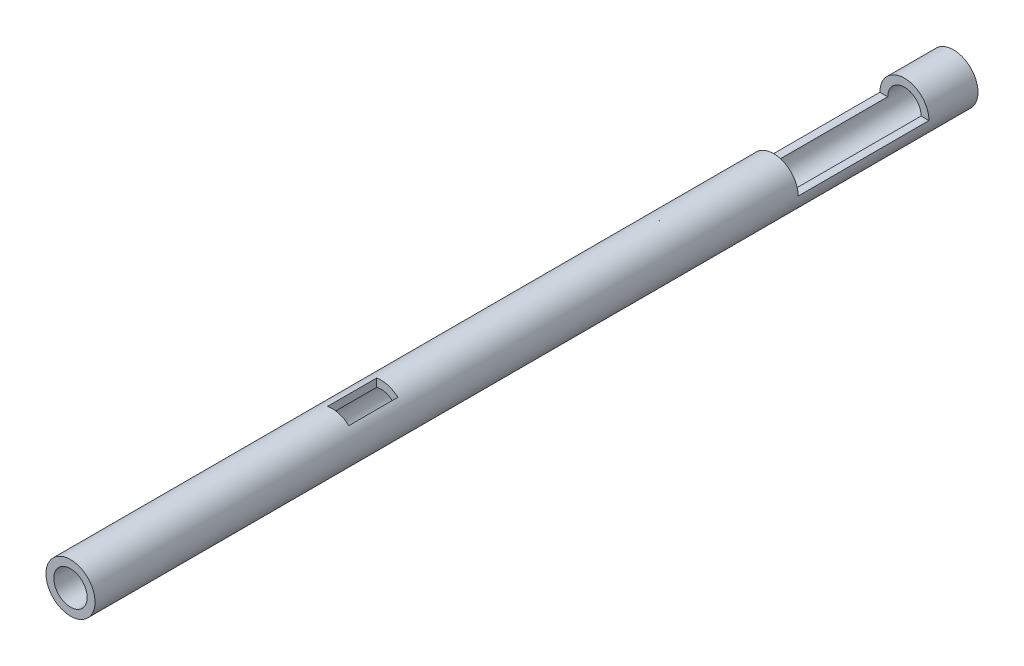
SolidWorks part; units mm, degrees
ref_plane "Front" through (0, 0, 0) normal (0, 0, 1) x (1, 0, 0)
ref_plane "Top" through (0, 0, 0) normal (0, 1, 0) x (1, 0, 0)
ref_plane "Right" through (0, 0, 0) normal (1, 0, 0) x (0, 0, -1)
sketch "Sketch2" plane through (0, 0, 0) normal (0, 0, 1) x (1, 0, 0)
  circle A0 centre (0, 0) radius 12.954
  circle A1 centre (0, 0) radius 19.05
  dimension "D1" = 38.1
  dimension "D2" = 25.908
extrude "Boss-Extrude1" add sketch "Sketch2" along normal blind 685.8
sketch "Sketch3" plane through (0, 0, 0) normal (0, 1, 0) x (1, 0, 0)
  line L0 (19.05, 0) -> (-19.05, 0) construction
  line L1 (-25.4, -38.1) -> (25.4, -38.1)
  line L2 (-25.4, -38.1) -> (-25.4, -139.7)
  line L3 (-25.4, -139.7) -> (25.4, -139.7)
  line L4 (25.4, -38.1) -> (25.4, -139.7)
  line L5 (-25.4, -38.1) -> (25.4, -139.7) construction
  line L6 (-25.4, -139.7) -> (25.4, -38.1) construction
  line L7 (0, 0) -> (0, -161.8795) construction
  point P4 (0, -88.9)
  dimension "D1" = 101.6
  dimension "D2" = 38.1
  dimension "D3" = 25.4
  dimension "D4" = 25.4
extrude "Cut-Extrude1" cut sketch "Sketch3" along normal up to next
sketch "Sketch4" plane through (0, 0, 0) normal (0, 1, 0) x (1, 0, 0)
  line L0 (0, -685.8) -> (0, -403.662) construction
  line L1 (-19.05, -685.8) -> (19.05, -685.8) construction
  line L2 (12.954, -444.5) -> (12.954, -482.6)
  line L3 (12.954, -482.6) -> (-3.556, -482.6)
  line L4 (-3.556, -482.6) -> (-3.556, -444.5)
  line L5 (-3.556, -444.5) -> (12.954, -444.5)
  dimension "D1" = 12.954
  dimension "D2" = 16.51
  dimension "D3" = 38.1
  dimension "D4" = 203.2
extrude "Cut-Extrude2" cut sketch "Sketch4" along normal up to next
